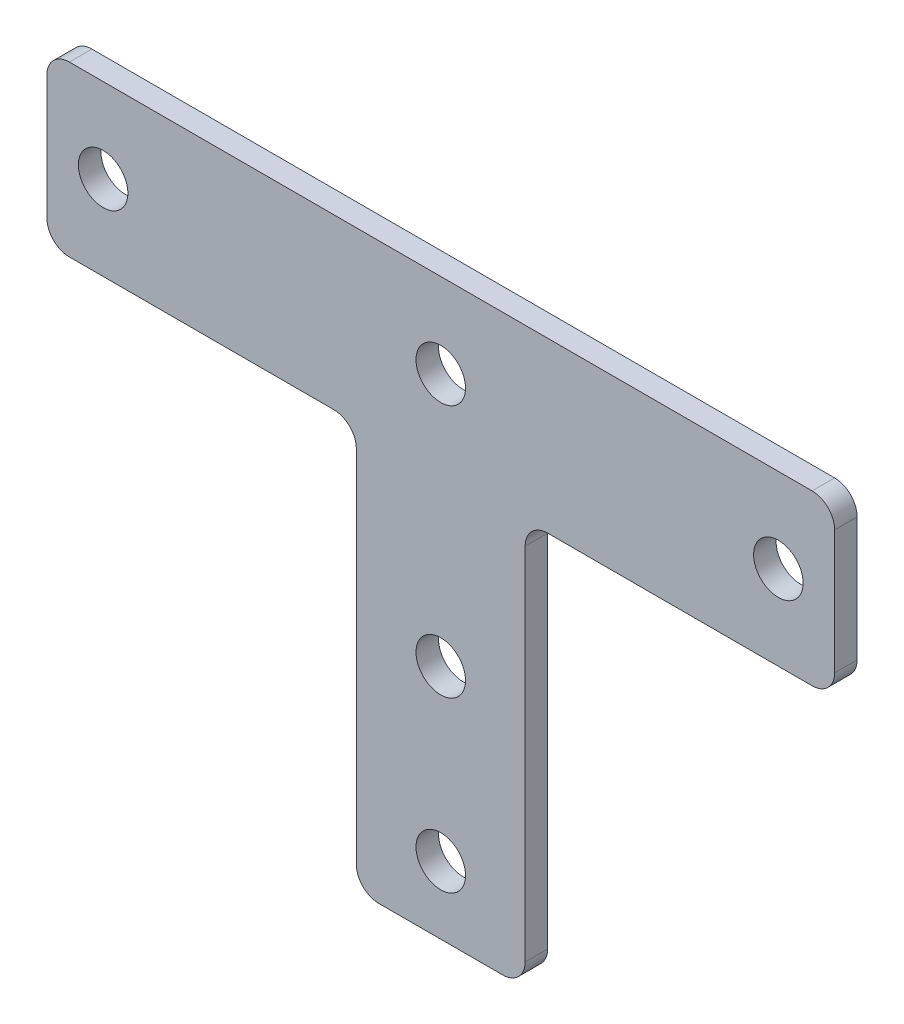
SolidWorks part; units mm, degrees
material "6061 合金"
ref_plane "前视基准面" through (0, 0, 0) normal (0, 0, 1) x (1, 0, 0)
ref_plane "上视基准面" through (0, 0, 0) normal (0, 1, 0) x (1, 0, 0)
ref_plane "右视基准面" through (0, 0, 0) normal (1, 0, 0) x (0, 0, -1)
other "Configuration Table"
sketch "草图1" plane through (0, 0, 0) normal (0, 0, 1) x (1, 0, 0)
  line L0 (35, 0) -> (35, -51) construction
  line L1 (0, 0) -> (70, 0)
  line L2 (0, 0) -> (0, -15)
  line L3 (0, -15) -> (70, -15)
  line L4 (70, 0) -> (70, -15)
  line L5 (27.5, 0) -> (42.5, 0)
  line L6 (27.5, 0) -> (27.5, -51)
  line L7 (27.5, -51) -> (42.5, -51)
  line L8 (42.5, 0) -> (42.5, -51)
  line L9 (0, -7.5) -> (70, -7.5) construction
  circle A0 centre (35, -7.5) radius 2.2
  circle A1 centre (65, -7.5) radius 2.2
  circle A2 centre (5, -7.5) radius 2.2
  circle A3 centre (35, -30) radius 2.2
  circle A4 centre (35, -45) radius 2.2
  dimension "D5" = 60
  dimension "D6" = 4.4
  dimension "D7" = 4.4
  dimension "D10" = 4.4
  dimension "D1" = 70
  dimension "D2" = 15
  dimension "D3" = 15
  dimension "D4" = 36
  dimension "D8" = 15
  dimension "D9" = 15
extrude "凸台-拉伸1" add sketch "草图1" along normal blind 2 contours L6 L1 L2 L3 A2 | L1 L8 L3 L4 A1 | L8 L1 L6 L3 A0 | L8 L3 L6 L7 A4 A3
fillet "圆角1" radius 2 8 edges at (70, -15, 1) (70, 0, 1) (42.5, -51, 1) (27.5, -51, 1) (0, 0, 1) (0, -15, 1) (27.5, -15, 1) (42.5, -15, 1)
